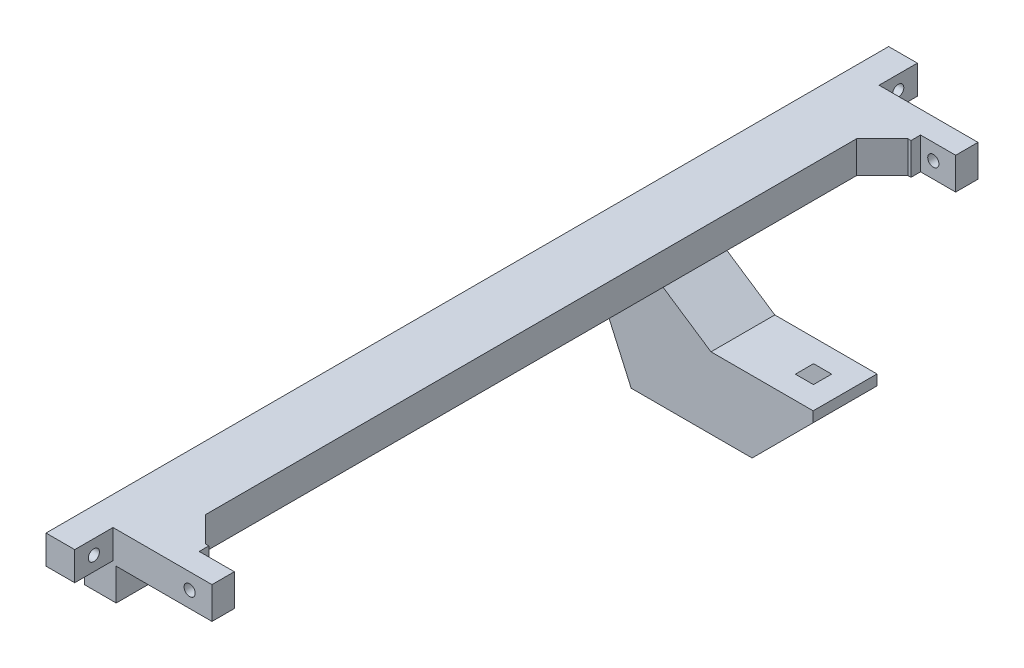
SolidWorks part; units mm, degrees
ref_plane "Front Plane" through (0, 0, 0) normal (0, 0, 1) x (1, 0, 0)
ref_plane "Top Plane" through (0, 0, 0) normal (0, 1, 0) x (1, 0, 0)
ref_plane "Right Plane" through (0, 0, 0) normal (1, 0, 0) x (0, 0, -1)
sketch "Sketch1" plane through (0, 0, 0) normal (0, 0, 1) x (1, 0, 0)
  line L0 (-10, 0) -> (0, 0)
  line L1 (0, 0) -> (0, 10)
  line L2 (0, 10) -> (10, 10)
  line L3 (10, 10) -> (10, 20)
  line L4 (10, 20) -> (-10, 20)
  line L5 (-10, 20) -> (-10, 0)
  dimension "D1" = 10
  dimension "D2" = 20
extrude "Boss-Extrude1" add sketch "Sketch1" along normal blind 240
sketch "Sketch4" plane through (0, 20, 0) normal (0, 1, 0) x (1, 0, 0)
  line L0 (10, 0) -> (30, 0)
  line L1 (30, 0) -> (30, -10)
  line L3 (10, -240) -> (10, 0) construction
  line L8 (10, -18) -> (10, 0)
  line L9 (30, -10) -> (18, -10)
  line L10 (18, -10) -> (10, -18)
  dimension "D1" = 45
  dimension "D2" = 10
  dimension "D3" = 12
  dimension "D4" = 20
extrude "Boss-Extrude3" add sketch "Sketch4" against normal up to surface (10 mm away) up to face at (5, 10, 120)
sketch "Sketch5" plane through (0, 0, 0) normal (0, 0, -1) x (-1, 0, 0)
  line L1 (-30, 10) -> (-30, 20) construction
  circle A0 centre (-23, 15) radius 1.75
  point P4 (-30, 15)
  dimension "D1" = 3.5
  dimension "D2" = 7
extrude "Cut-Extrude1" cut sketch "Sketch5" against normal through all
sketch "Sketch6" plane through (30, 0, 0) normal (1, 0, 0) x (0, 0, -1)
  line L6 (-14, 21) -> (-7, 21)
  line L7 (-14, 21) -> (-14, 9)
  line L8 (-14, 9) -> (-7, 9)
  line L9 (-7, 21) -> (-7, 9)
  line L10 (0, 10) -> (0, 20) construction
  point P7 (0, 15)
  point P8 (-7, 15)
  dimension "D1" = 12
  dimension "D2" = 7
  dimension "D3" = 7
extrude "Cut-Extrude2" cut sketch "Sketch6" against normal blind 11
ref_plane "Plane1" through (0, 0, 120) normal (0, 0, -1) x (-1, 0, 0)
mirror "Mirror1" about plane through (0, 0, 120) normal (0, 0, -1) of "Cut-Extrude1", "Boss-Extrude3", "Cut-Extrude2"
sketch "Sketch7" plane through (0, 0, 0) normal (1, 0, 0) x (0, 0, -1)
  line L0 (-68.66, 20) -> (-68.66, -12.38) construction
  line L1 (-222, 20) -> (-18, 20) construction
  line L2 (0, 0) -> (0, 10) construction
  line L3 (-240, 0) -> (0, 0) construction
  line L8 (-78.66, -22.38) -> (-58.66, -22.38)
  line L9 (-78.66, -22.38) -> (-78.66, 0)
  line L10 (-78.66, 0) -> (-58.66, 0)
  line L11 (-58.66, -22.38) -> (-58.66, 0)
  line L12 (-68.66, -12.38) -> (-78.66, -12.38) construction
  line L13 (-68.66, -12.38) -> (-68.66, -22.38) construction
  point P12 (-68.66, -22.38)
  dimension "D1" = 22.38
  dimension "D2" = 68.66
  dimension "D3" = 10
extrude "Boss-Extrude4" add sketch "Sketch7" along normal blind 57.02
sketch "Sketch9" plane through (0, 0, 58.66) normal (0, 0, -1) x (-1, 0, 0)
  line L0 (10, 20) -> (10, 0) construction
  line L3 (-10, 10) -> (10, 10)
  line L6 (-10, 10) -> (-25, 0)
  line L7 (-57.02, 0) -> (0, 0) construction
  line L8 (-25, 0) -> (-25, -22.38)
  line L9 (-25, -22.38) -> (0, -22.38)
  line L10 (-57.02, -22.38) -> (0, -22.38) construction
  line L11 (0, 0) -> (0, 10) construction
  line L12 (0, -22.38) -> (10, 0)
  line L13 (10, 0) -> (10, 10)
  dimension "D1" = 25
  dimension "D2" = 20
extrude "Boss-Extrude5" add sketch "Sketch9" against normal up to surface (20 mm away) up to face at (28.51, -11.19, 78.66)
sketch "Sketch10" plane through (0, 0, 58.66) normal (0, 0, -1) x (-1, 0, 0)
  line L6 (-31.6672, -28.6015) -> (-43.135, -40.0692)
  line L7 (-43.135, -40.0692) -> (-74.5316, -8.6727)
  line L8 (-74.5316, -8.6727) -> (-63.0638, 2.7951)
  line L10 (-63.0638, 2.7951) -> (-31.6672, -28.6015)
extrude "Cut-Extrude3" cut sketch "Sketch10" against normal up to surface (20 mm away) up to face at (17.38, -3.095, 78.66)
ref_plane "Plane2" through (26.5988, -26.5988, 0) normal (0.7071, -0.7071, 0) x (-0.7071, -0.7071, 0)
sketch "Sketch14" plane through (0, 0, 0) normal (0, 0, -1) x (-1, 0, 0)
  line L1 (10, 20) -> (1, 20)
  line L2 (10, 20) -> (10, 11)
  line L3 (10, 11) -> (1, 11)
  line L4 (1, 20) -> (1, 11)
  dimension "D1" = 9
extrude "Boss-Extrude6" add sketch "Sketch14" along normal blind 12
sketch "Sketch15" plane through (0, 0, 240) normal (0, 0, 1) x (1, 0, 0)
  line L1 (-10, 20) -> (-1, 20)
  line L2 (-10, 20) -> (-10, 11)
  line L3 (-10, 11) -> (-1, 11)
  line L4 (-1, 20) -> (-1, 11)
  dimension "D1" = 9
extrude "Boss-Extrude7" add sketch "Sketch15" along normal blind 12
sketch "Sketch18" plane through (-10, 0, 0) normal (-1, 0, 0) x (0, 0, 1)
  line L0 (-12, 11) -> (-12, 20) construction
  line L1 (246, 15.5) -> (252, 15.5) construction
  line L2 (252, 20) -> (252, 11) construction
  line L3 (-6, 15.5) -> (-12, 15.5) construction
  circle A0 centre (-6, 15.5) radius 1.75
  circle A1 centre (246, 15.5) radius 1.75
  point P4 (-12, 15.5)
  dimension "D1" = 3.5
  dimension "D2" = 6
extrude "Cut-Extrude10" cut sketch "Sketch18" against normal up to surface (9 mm away) up to face at (-1, 15.5, -6)
sketch "Sketch19" plane through (-10, 0, 0) normal (-1, 0, 0) x (0, 0, 1)
  circle A0 centre (-6, 15.5) radius 3
  circle A1 centre (246, 15.5) radius 3
  dimension "D1" = 6
extrude "Cut-Extrude11" cut sketch "Sketch19" against normal blind 3.1
sketch "Sketch20" plane through (-10, 0, 0) normal (-1, 0, 0) x (0, 0, 1)
  line L0 (240, 0) -> (78.66, 0) construction
  line L2 (240, 11) -> (240, 0) construction
  circle A0 centre (140, 5) radius 1.75
  dimension "D1" = 3.5
  dimension "D2" = 5
  dimension "D3" = 100
extrude "Cut-Extrude12" cut sketch "Sketch20" against normal up to surface (10 mm away) up to face at (0, 5, 159.33)
sketch "Sketch21" plane through (-10, 0, 0) normal (-1, 0, 0) x (0, 0, 1)
  line L0 (240, 0) -> (78.66, 0) construction
  line L1 (141.6454, 2.15) -> (143.2909, 5)
  line L2 (143.2909, 5) -> (141.6454, 7.85)
  line L3 (141.6454, 7.85) -> (138.3546, 7.85)
  line L4 (138.3546, 7.85) -> (136.7091, 5)
  line L5 (136.7091, 5) -> (138.3546, 2.15)
  line L6 (138.3546, 2.15) -> (141.6454, 2.15)
  circle A0 centre (140, 5) radius 2.85 construction
  dimension "D1" = 5.7
extrude "Cut-Extrude13" cut sketch "Sketch21" against normal blind 2.1
ref_plane "Plane3" through (0, 0, 0) normal (0.7071, 0.7071, 0) x (0.7071, -0.7071, 0)
sketch "Sketch22" plane through (30.1344, -30.1344, 0) normal (0.7071, -0.7071, 0) x (0, 0, -1)
  line L0 (-78.66, 38.022) -> (-78.66, 10.9663) construction
  line L2 (-78.66, 38.022) -> (-58.66, 38.022) construction
  circle A0 centre (-68.66, 24.452) radius 1.75
  dimension "D1" = 3.5
  dimension "D2" = 10
  dimension "D3" = 13.57
extrude "Cut-Extrude14" cut sketch "Sketch22" against normal blind 15
sketch "Sketch24" plane through (0, 0, 0) normal (0.7071, 0.7071, 0) x (0.7071, -0.7071, 0)
  line L1 (31.3192, -65.81) -> (35.3192, -65.81)
  line L2 (31.3192, -65.81) -> (31.3192, -71.51)
  line L3 (31.3192, -71.51) -> (35.3192, -71.51)
  line L4 (35.3192, -65.81) -> (35.3192, -71.51)
  line L5 (40.3192, -58.66) -> (17.6777, -58.66) construction
  line L6 (40.3192, -58.66) -> (40.3192, -78.66) construction
  point P6 (31.3192, -68.66)
  dimension "D1" = 4
  dimension "D2" = 5.7
  dimension "D3" = 10
  dimension "D4" = 5
extrude "Cut-Extrude15" cut sketch "Sketch24" along normal through all
